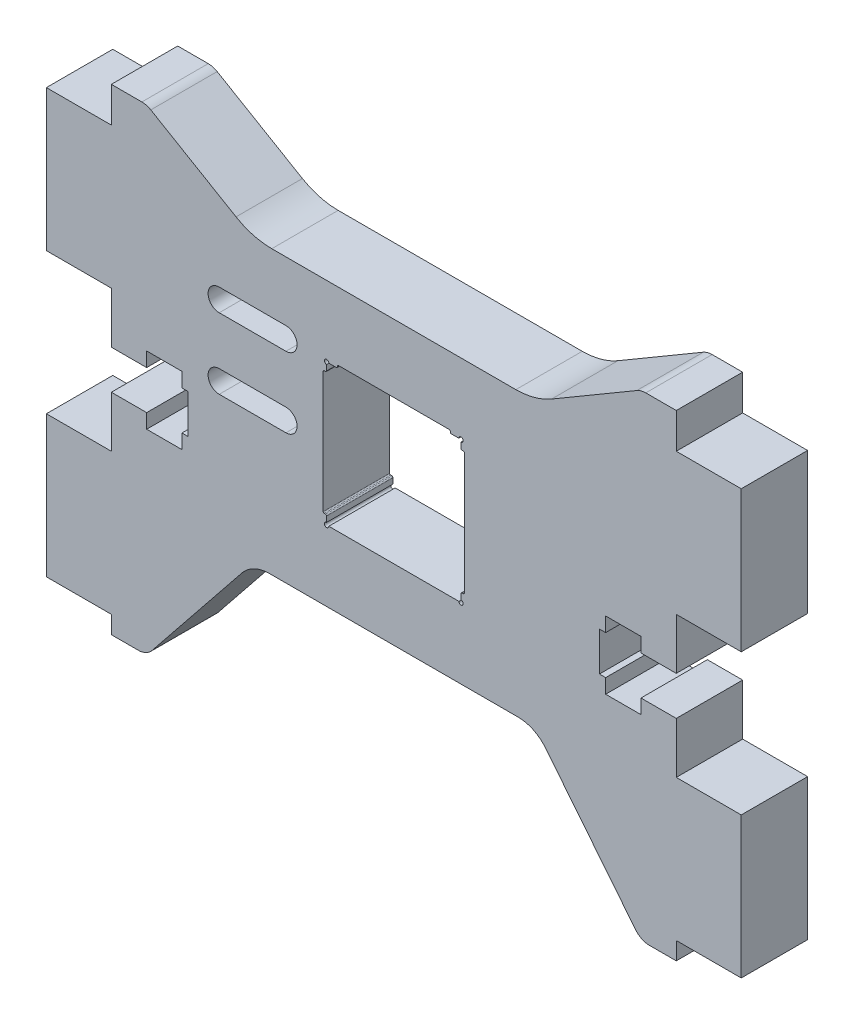
SolidWorks part; units mm, degrees
ref_plane "Front Plane" through (0, 0, 0) normal (0, 0, 1) x (1, 0, 0)
ref_plane "Top Plane" through (0, 0, 0) normal (0, 1, 0) x (1, 0, 0)
ref_plane "Right Plane" through (0, 0, 0) normal (1, 0, 0) x (0, 0, -1)
sketch "Sketch1" plane through (0, 0, 0) normal (0, 0, 1) x (1, 0, 0)
  line L0 (0, 0) -> (0, -22.987) construction
  line L1 (6.0452, -6.35) -> (-6.0452, -6.35)
  line L2 (6.0452, -6.35) -> (6.0452, 6.35)
  line L3 (6.0452, 6.35) -> (-6.0452, 6.35)
  line L4 (-6.0452, -6.35) -> (-6.0452, 6.35)
  line L5 (6.0452, -6.35) -> (-6.0452, 6.35) construction
  line L6 (6.0452, 6.35) -> (-6.0452, -6.35) construction
  line L7 (25.4, -22.987) -> (-25.4, -22.987) construction
  line L8 (25.4, 2.413) -> (25.4, -10.287)
  line L9 (25.4, -22.987) -> (31.242, -22.987)
  line L10 (-31.242, 2.413) -> (-25.4, 2.413)
  line L11 (31.242, -10.287) -> (25.4, -10.287)
  line L12 (31.242, -22.987) -> (31.242, -10.287)
  line L13 (25.4, -22.987) -> (25.4, -24.5745)
  line L14 (-12.7, -12.7) -> (12.7, -12.7)
  line L15 (12.7, -12.7) -> (22.225, -24.5745)
  line L16 (22.225, -24.5745) -> (25.4, -24.5745)
  line L17 (-12.7, 12.7) -> (12.7, 12.7)
  line L18 (-12.7, 12.7) -> (-22.225, 18.288)
  line L19 (-31.242, -10.287) -> (-25.4, -10.287)
  line L20 (-31.242, -22.987) -> (-31.242, -10.287)
  line L21 (-25.4, -22.987) -> (-31.242, -22.987)
  line L22 (-25.4, -22.987) -> (-25.4, -24.5745)
  line L23 (-22.225, -24.5745) -> (-25.4, -24.5745)
  line L24 (-12.7, -12.7) -> (-22.225, -24.5745)
  line L25 (-25.4, 18.288) -> (-22.225, 18.288)
  line L26 (-25.4, 2.413) -> (-25.4, -10.287)
  line L27 (31.242, 2.413) -> (25.4, 2.413)
  line L28 (31.242, 2.413) -> (31.242, 15.113)
  line L29 (31.242, 15.113) -> (25.4, 15.113)
  line L30 (25.4, 15.113) -> (25.4, 18.288)
  line L31 (25.4, 18.288) -> (22.225, 18.288)
  line L32 (-25.4, 15.113) -> (-25.4, 18.288)
  line L33 (12.7, 12.7) -> (22.225, 18.288)
  line L34 (-31.242, 15.113) -> (-25.4, 15.113)
  line L35 (-31.242, 2.413) -> (-31.242, 15.113)
  point P0 (0, 0)
  point P11 (0, -22.987)
  point P28 (0, -12.7)
  point P29 (0, 12.7)
  dimension "D1" = 12.7
  dimension "D2" = 12.0904
  dimension "D3" = 16.637
  dimension "D4" = 50.8
  dimension "D5" = 12.7
  dimension "D6" = 5.842
  dimension "D7" = 12.7
  dimension "D8" = 1.5875
  dimension "D9" = 12.7
  dimension "D10" = 6.35
  dimension "D11" = 3.175
  dimension "D12" = 6.35
  dimension "D13" = 12.7
  dimension "D16" = 12.7
  dimension "D17" = 3.175
  dimension "D18" = 3.175
extrude "Boss-Extrude1" add sketch "Sketch1" along normal blind 5.969
sketch "Sketch2" plane through (0, 0, 5.969) normal (0, 0, 1) x (1, 0, 0)
  line L0 (-25.4, -3.937) -> (25.4, -3.937) construction
  line L1 (-25.4, 2.413) -> (-25.4, -10.287) construction
  line L2 (25.4, -10.287) -> (25.4, 2.413) construction
  line L3 (22.225, -2.1844) -> (22.225, -0.889)
  line L4 (22.225, -5.6896) -> (25.4, -5.6896)
  line L5 (0, -3.937) -> (0, -12.7) construction
  line L6 (22.225, -2.1844) -> (25.4, -2.1844)
  line L7 (25.4, -5.6896) -> (25.4, -2.1844)
  line L8 (22.225, -5.6896) -> (25.4, -2.1844) construction
  line L9 (22.225, -2.1844) -> (25.4, -5.6896) construction
  line L10 (19.05, -6.985) -> (22.225, -6.985)
  line L11 (19.05, -6.985) -> (19.05, -5.6896)
  line L12 (19.05, -0.889) -> (22.225, -0.889)
  line L13 (22.225, -6.985) -> (22.225, -5.6896)
  line L14 (19.05, -6.985) -> (22.225, -0.889) construction
  line L15 (19.05, -0.889) -> (22.225, -6.985) construction
  line L16 (18.492, -5.6896) -> (19.05, -5.6896)
  line L17 (18.492, -5.6896) -> (18.492, -2.1844)
  line L18 (18.492, -2.1844) -> (19.05, -2.1844)
  line L19 (-12.7, -12.7) -> (12.7, -12.7) construction
  line L20 (18.492, -5.6896) -> (19.05, -2.1844) construction
  line L21 (18.492, -2.1844) -> (19.05, -5.6896) construction
  line L22 (19.05, -2.1844) -> (19.05, -0.889)
  line L23 (-18.492, -2.1844) -> (-19.05, -5.6896) construction
  line L24 (-18.492, -5.6896) -> (-19.05, -2.1844) construction
  line L25 (-19.05, -0.889) -> (-22.225, -6.985) construction
  line L26 (-19.05, -6.985) -> (-22.225, -0.889) construction
  line L27 (-22.225, -2.1844) -> (-25.4, -5.6896) construction
  line L28 (-22.225, -5.6896) -> (-25.4, -2.1844) construction
  line L29 (-19.05, -2.1844) -> (-19.05, -0.889)
  line L30 (-18.492, -2.1844) -> (-19.05, -2.1844)
  line L31 (-18.492, -5.6896) -> (-18.492, -2.1844)
  line L32 (-18.492, -5.6896) -> (-19.05, -5.6896)
  line L33 (-22.225, -6.985) -> (-22.225, -5.6896)
  line L34 (-19.05, -0.889) -> (-22.225, -0.889)
  line L35 (-19.05, -6.985) -> (-19.05, -5.6896)
  line L36 (-19.05, -6.985) -> (-22.225, -6.985)
  line L37 (-25.4, -5.6896) -> (-25.4, -2.1844)
  line L38 (-22.225, -2.1844) -> (-25.4, -2.1844)
  line L39 (-22.225, -5.6896) -> (-25.4, -5.6896)
  line L40 (-22.225, -2.1844) -> (-22.225, -0.889)
  point P6 (23.8125, -3.937)
  point P11 (20.6375, -3.937)
  point P16 (18.771, -3.937)
  point P37 (-18.771, -3.937)
  point P38 (-20.6375, -3.937)
  point P39 (-23.8125, -3.937)
  dimension "D1" = 3.175
  dimension "D2" = 3.175
  dimension "D3" = 3.5052
  dimension "D4" = 6.096
  dimension "D5" = 0.558
extrude "Cut-Extrude1" cut sketch "Sketch2" against normal through all
sketch "Sketch3" plane through (0, 0, 5.969) normal (0, 0, 1) x (1, 0, 0)
  line L0 (-6.0452, 0) -> (6.0452, 0) construction
  line L1 (-6.0452, 6.35) -> (-6.0452, -6.35) construction
  line L2 (6.0452, -6.35) -> (6.0452, 6.35) construction
  circle A0 centre (6.0452, 6.35) radius 0.1984
  circle A1 centre (-6.0452, 6.35) radius 0.1984
  circle A2 centre (-6.0452, -6.35) radius 0.1984
  circle A3 centre (6.0452, -6.35) radius 0.1984
  dimension "D1" = 0.3969
  dimension "D2" = 0.3969
extrude "Cut-Extrude2" cut sketch "Sketch3" against normal through all
fillet "Fillet1" radius 3.175 2 edges at (-12.7, -12.7, 2.9845) (12.7, -12.7, 2.9845)
fillet "Fillet2" radius 1.5875 4 edges at (22.225, -24.5745, 2.9845) (-22.225, -24.5745, 2.9845) (-22.225, 18.288, 2.9845) (22.225, 18.288, 2.9845)
sketch "Sketch4" plane through (0, 0, 5.969) normal (0, 0, 1) x (1, 0, 0)
  line L0 (-6.0452, 0) -> (6.0452, 0) construction
  line L1 (-6.0452, 6.1516) -> (-6.0452, -6.1516) construction
  line L2 (6.0452, -6.1516) -> (6.0452, 6.1516) construction
  line L4 (6.35, -5.5562) -> (-6.35, -5.5563)
  line L5 (6.35, -5.5562) -> (6.35, 5.5563)
  line L6 (6.35, 5.5563) -> (-6.35, 5.5562)
  line L7 (-6.35, -5.5563) -> (-6.35, 5.5562)
  line L8 (6.35, -5.5562) -> (-6.35, 5.5562) construction
  line L9 (6.35, 5.5563) -> (-6.35, -5.5563) construction
  point P6 (0, 0)
  dimension "D1" = 12.7
  dimension "D2" = 11.1125
extrude "Cut-Extrude3" cut sketch "Sketch4" against normal through all
fillet "Fillet7" radius 0.1 8 edges at (6.35, -5.5562, 2.9845) (6.0452, -5.5562, 2.9845) (6.35, 5.5563, 2.9845) (6.0452, 5.5563, 2.9845) (-6.0452, 5.5562, 2.9845) (-6.35, 5.5562, 2.9845) (-6.35, -5.5563, 2.9845) (-6.0452, -5.5563, 2.9845)
sketch "Sketch5" plane through (0, 0, 5.969) normal (0, 0, 1) x (1, 0, 0)
  line L0 (5.8468, 6.35) -> (-5.8468, 6.35) construction
  line L1 (5.08, 6.1) -> (-5.08, 6.1)
  line L2 (5.08, 6.1) -> (5.08, 6.6)
  line L3 (5.08, 6.6) -> (-5.08, 6.6)
  line L4 (-5.08, 6.1) -> (-5.08, 6.6)
  line L5 (5.08, 6.1) -> (-5.08, 6.6) construction
  line L6 (5.08, 6.6) -> (-5.08, 6.1) construction
  point P0 (0, 6.35)
  dimension "D1" = 10.16
  dimension "D2" = 0.5
extrude "Cut-Extrude4" cut sketch "Sketch5" against normal through all
fillet "Fillet8" radius 0.1 4 edges at (5.08, 6.6, 2.9845) (5.08, 6.35, 2.9845) (-5.08, 6.6, 2.9845) (-5.08, 6.35, 2.9845)
sketch "Sketch6" plane through (0, 0, 5.969) normal (0, 0, 1) x (1, 0, 0)
  line L0 (-12.7, 12.7) -> (-12.7, -12.7) construction
  line L1 (12.7, 12.7) -> (-12.7, 12.7) construction
  line L2 (-11.1766, -12.7) -> (11.1766, -12.7) construction
  line L3 (-15.7, 6.35) -> (-9.7, 6.35) construction
  line L4 (-15.7, 7.35) -> (-9.7, 7.35)
  line L5 (-15.7, 5.35) -> (-9.7, 5.35)
  line L6 (-15.7, 0) -> (-9.7, 0) construction
  line L7 (-15.7, 1) -> (-9.7, 1)
  line L8 (-15.7, -1) -> (-9.7, -1)
  arc A0 (-15.7, 7.35) -> (-15.7, 5.35) centre (-15.7, 6.35) ccw
  arc A1 (-9.7, 5.35) -> (-9.7, 7.35) centre (-9.7, 6.35) ccw
  arc A2 (-15.7, 1) -> (-15.7, -1) centre (-15.7, 0) ccw
  arc A3 (-9.7, -1) -> (-9.7, 1) centre (-9.7, 0) ccw
  point P8 (-12.7, 6.35)
  point P17 (-12.7, 0)
  point P18 (-12.7, -2.413)
  dimension "D2" = 1
  dimension "D1" = 6
  dimension "D3" = 12.7
  dimension "D5" = 6.35
extrude "Cut-Extrude5" cut sketch "Sketch6" against normal through all
fillet "Fillet9" radius 6.35 2 edges at (12.7, 12.7, 2.9845) (-12.7, 12.7, 2.9845)
